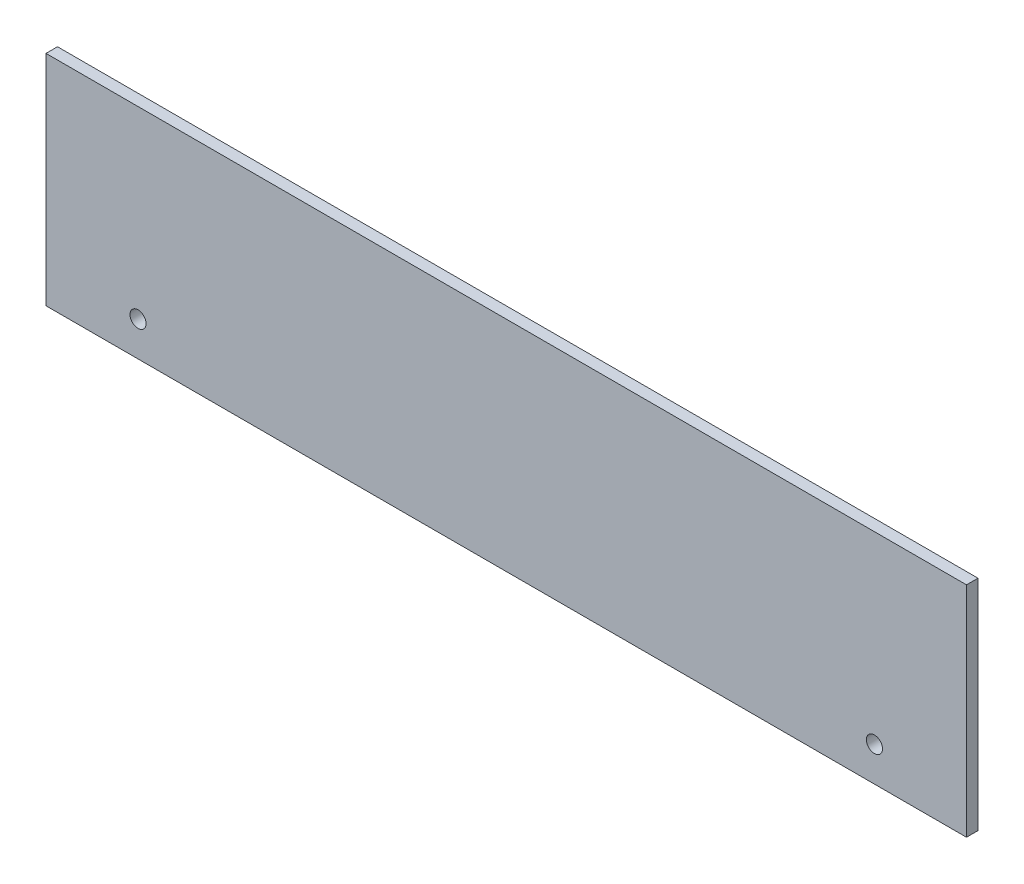
SolidWorks part; units mm, degrees
material "ABS PC"
ref_plane "前视基准面" through (0, 0, 0) normal (0, 0, 1) x (1, 0, 0)
ref_plane "上视基准面" through (0, 0, 0) normal (0, 1, 0) x (1, 0, 0)
ref_plane "右视基准面" through (0, 0, 0) normal (1, 0, 0) x (0, 0, -1)
other "Configuration Table"
sketch "草图1" plane through (0, 0, 0) normal (0, 0, 1) x (1, 0, 0)
  line L0 (-26.1056, -107.9524) -> (-26.1056, 53.7547) construction
  line L1 (-226.1056, -107.9524) -> (173.8944, -107.9524)
  line L2 (-226.1056, -107.9524) -> (-226.1056, -202.9524)
  line L3 (-226.1056, -202.9524) -> (-53.6056, -202.9524)
  line L4 (173.8944, -107.9524) -> (173.8944, -202.9524)
  line L5 (121.3944, -202.9524) -> (173.8944, -202.9524)
  line L6 (1.3944, -170.9524) -> (121.3944, -170.9524) construction
  line L7 (1.3944, -170.9524) -> (1.3944, -202.9524) construction
  line L9 (121.3944, -170.9524) -> (121.3944, -202.9524) construction
  line L13 (1.3944, -202.9524) -> (121.3944, -202.9524)
  line L14 (-53.6056, -202.9524) -> (1.3944, -202.9524)
  line L15 (173.8944, -187.9524) -> (-226.1056, -187.9524) construction
  circle A0 centre (-186.1056, -187.9524) radius 3.5
  circle A1 centre (133.8944, -187.9524) radius 3.5
  dimension "D6" = 7
  dimension "D1" = 400
  dimension "D2" = 95
  dimension "D3" = 27.5
  dimension "D4" = 120
  dimension "D5" = 32
  dimension "D7" = 40
  dimension "D8" = 15
extrude "凸台-拉伸1" add sketch "草图1" along normal blind 5
